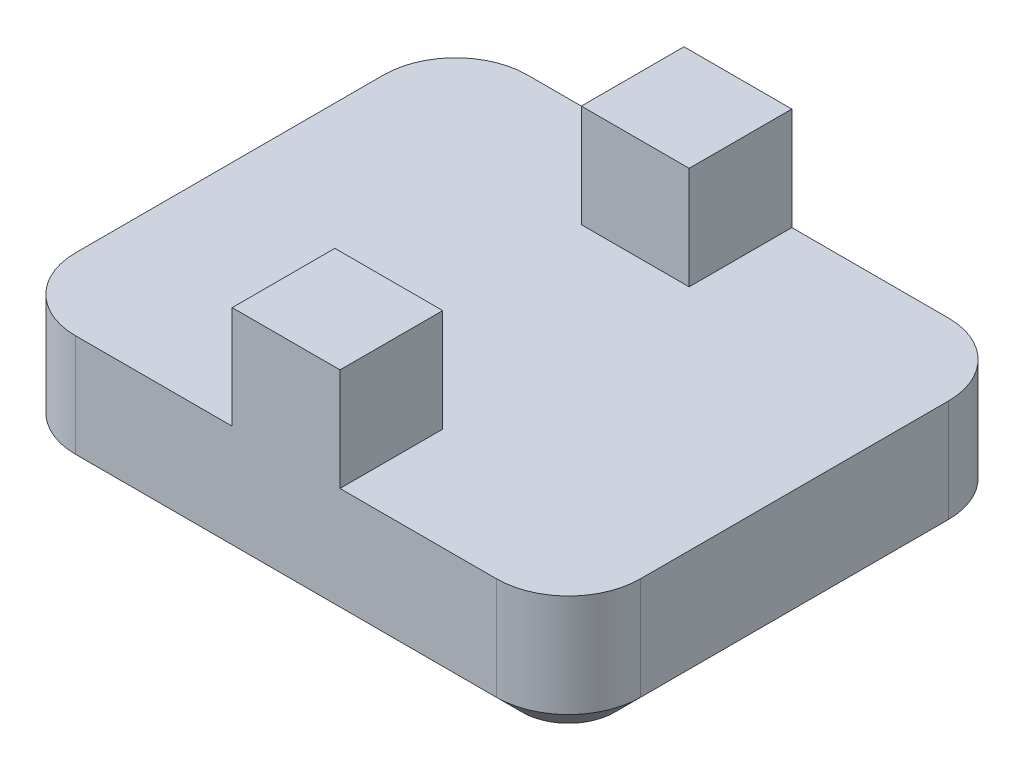
SolidWorks part; units mm, degrees
ref_plane "前视基准面" through (0, 0, 0) normal (0, 0, 1) x (1, 0, 0)
ref_plane "上视基准面" through (0, 0, 0) normal (0, 1, 0) x (1, 0, 0)
ref_plane "右视基准面" through (0, 0, 0) normal (1, 0, 0) x (0, 0, -1)
other "Configuration Table"
sketch "草图1" plane through (0, 0, 0) normal (0, 1, 0) x (1, 0, 0)
  line L1 (-53.1928, -6.9872) -> (-44.9928, -6.9872)
  line L2 (-54.5928, -8.3872) -> (-54.5928, -14.3872)
  line L3 (-53.1928, -15.7872) -> (-44.9928, -15.7872)
  line L4 (-43.5928, -8.3872) -> (-43.5928, -14.3872)
  line L5 (-43.5928, -14.3872) -> (-43.5928, -8.3872) construction
  line L7 (-54.5928, -14.3872) -> (-54.5928, -12.8872) construction
  line L8 (-50.2428, -6.9872) -> (-58.4211, -6.9872) construction
  line L9 (-58.4211, -15.7872) -> (-50.2428, -15.7872) construction
  arc A0 (-44.9928, -15.7872) -> (-43.5928, -14.3872) centre (-44.9928, -14.3872) ccw
  arc A1 (-54.5928, -14.3872) -> (-53.1928, -15.7872) centre (-53.1928, -14.3872) ccw
  arc A2 (-44.9928, -6.9872) -> (-43.5928, -8.3872) centre (-44.9928, -8.3872) cw
  arc A3 (-53.1928, -6.9872) -> (-54.5928, -8.3872) centre (-53.1928, -8.3872) ccw
  dimension "D1" = 1.4
extrude "凸台-拉伸1" add sketch "草图1" along normal blind 2.5
chamfer "倒角1" distance 0.5 angle 45 8 edges at (-49.0928, 0, 6.9872) (-54.1828, 0, 7.3972) (-44.0029, 0, 7.3972) (-54.5928, 0, 11.3872) (-43.5928, 0, 11.3872) (-54.1828, 0, 15.3771) (-44.0029, 0, 15.3771) (-49.0928, 0, 15.7872)
sketch "草图2" plane through (0, 2.5, 0) normal (0, 1, 0) x (1, 0, 0)
  line L0 (-44.9928, -6.9872) -> (-53.1928, -6.9872) construction
  line L1 (-50.1428, -6.9872) -> (-48.0428, -6.9872)
  line L2 (-50.1428, -6.9872) -> (-50.1428, -8.9872)
  line L3 (-50.1428, -8.9872) -> (-48.0428, -8.9872)
  line L4 (-48.0428, -6.9872) -> (-48.0428, -8.9872)
  line L5 (-53.1928, -15.7872) -> (-44.9928, -15.7872) construction
  line L6 (-50.1428, -13.7872) -> (-48.0428, -13.7872)
  line L7 (-50.1428, -13.7872) -> (-50.1428, -15.7872)
  line L8 (-50.1428, -15.7872) -> (-48.0428, -15.7872)
  line L9 (-48.0428, -13.7872) -> (-48.0428, -15.7872)
  point P6 (-49.0928, -6.9872)
  point P7 (-49.0928, -6.9872)
  point P14 (-49.0928, -15.7872)
  point P15 (-49.0928, -15.7872)
  dimension "D1" = 2.1
  dimension "D2" = 2
extrude "凸台-拉伸2" add sketch "草图2" along normal blind 2
